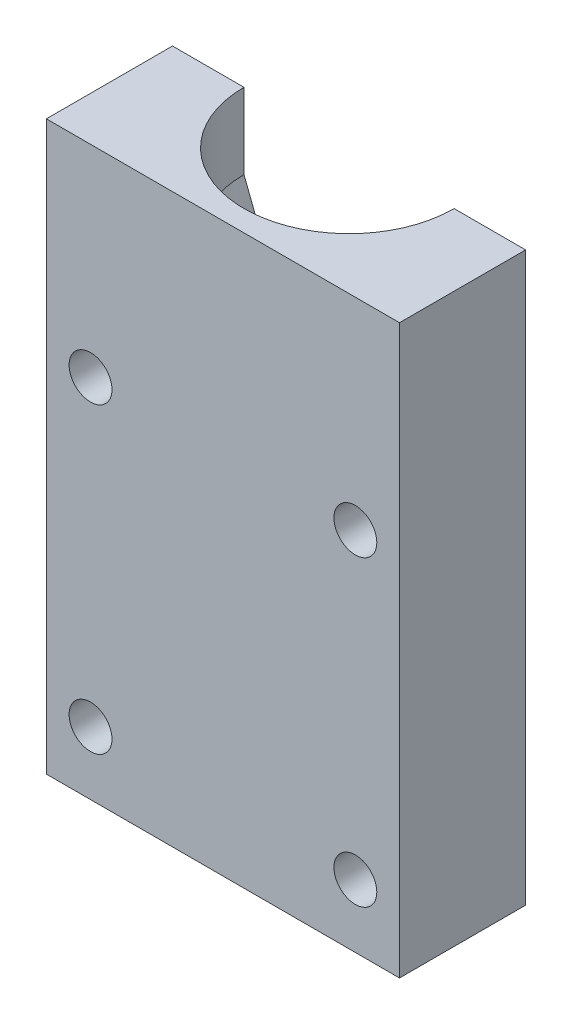
SolidWorks part; units mm, degrees
ref_plane "Front Plane" through (0, 0, 0) normal (0, 0, 1) x (1, 0, 0)
ref_plane "Top Plane" through (0, 0, 0) normal (0, 1, 0) x (1, 0, 0)
ref_plane "Right Plane" through (0, 0, 0) normal (1, 0, 0) x (0, 0, -1)
sketch "Sketch4" plane through (0, 0, 0) normal (0, 0, 1) x (1, 0, 0)
  line L1 (-14, 22.5) -> (14, 22.5)
  line L2 (-14, 22.5) -> (-14, -22.5)
  line L3 (-14, -22.5) -> (14, -22.5)
  line L4 (14, 22.5) -> (14, -22.5)
  line L5 (-14, 22.5) -> (14, -22.5) construction
  line L6 (-14, -22.5) -> (14, 22.5) construction
  point P0 (0, 0)
  dimension "D1" = 28
  dimension "D2" = 45
extrude "Boss-Extrude2" add sketch "Sketch4" along normal blind 10
sketch "Sketch5" plane through (0, 0, 0) normal (0, 0, 1) x (1, 0, 0)
  line L0 (0, 0) -> (0, 24.6891) construction
  line L1 (14, 22.5) -> (-14, 22.5) construction
  line L2 (-14, -22.5) -> (14, -22.5) construction
  line L3 (0, 22.5) -> (8.33, 22.5)
  line L4 (8.33, 22.5) -> (8.33, 16.5)
  line L5 (8.33, 16.5) -> (6, 10.5)
  line L6 (6, 10.5) -> (4.75, -18.71)
  line L7 (4.75, -18.71) -> (4.75, -22.5)
  line L8 (4.75, -22.5) -> (0, -22.5)
  line L10 (0, 22.5) -> (0, -22.5)
  dimension "D1" = 6
  dimension "D2" = 6
  dimension "D3" = 41.21
  dimension "D4" = 16.66
  dimension "D5" = 12
  dimension "D6" = 9.5
revolve "Cut-Revolve1" cut sketch "Sketch5" angle 360 about L0
sketch "Sketch6" plane through (0, 0, 10) normal (0, 0, 1) x (1, 0, 0)
  line L0 (-10.5, 22.5) -> (-10.5, -22.5) construction
  line L1 (14, 22.5) -> (-14, 22.5) construction
  line L2 (-14, -22.5) -> (14, -22.5) construction
  line L3 (10.5, 22.5) -> (10.5, -22.5) construction
  line L4 (14, 22.5) -> (-14, 22.5) construction
  line L5 (-14, -22.5) -> (14, -22.5) construction
  line L6 (-14, 22.5) -> (-14, -22.5) construction
  line L7 (0, 0) -> (0, 27.9587) construction
  circle A0 centre (-10.5, 6.5) radius 1.7
  circle A1 centre (-10.5, -17.5) radius 1.7
  circle A2 centre (10.5, 6.5) radius 1.7
  circle A3 centre (10.5, -17.5) radius 1.7
  dimension "D1" = 3.4
  dimension "D2" = 5
  dimension "D3" = 16
  dimension "D4" = 3.5
extrude "Cut-Extrude1" cut sketch "Sketch6" against normal through all
